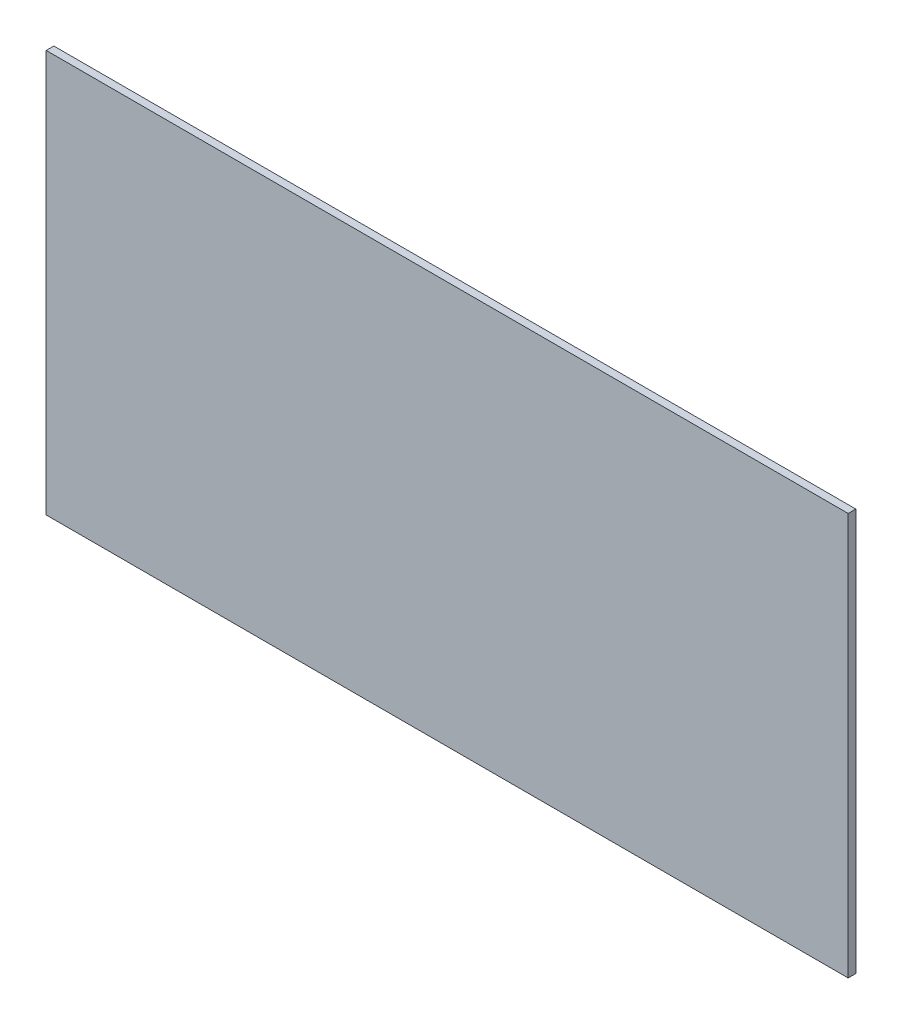
SolidWorks part; units mm, degrees
ref_plane "Front" through (0, 0, 0) normal (0, 0, 1) x (1, 0, 0)
ref_plane "Top" through (0, 0, 0) normal (0, 1, 0) x (1, 0, 0)
ref_plane "Right" through (0, 0, 0) normal (1, 0, 0) x (0, 0, -1)
sketch "Sketch1" plane through (0, 0, 0) normal (0, 0, 1) x (1, 0, 0)
  line L1 (-50.5877, 33.8583) -> (54.356, 33.8583)
  line L2 (-50.5877, 33.8583) -> (-50.5877, -18.7848)
  line L3 (-50.5877, -18.7848) -> (54.356, -18.7848)
  line L4 (54.356, 33.8583) -> (54.356, -18.7848)
extrude "Boss-Extrude1" add sketch "Sketch1" along normal blind 1
